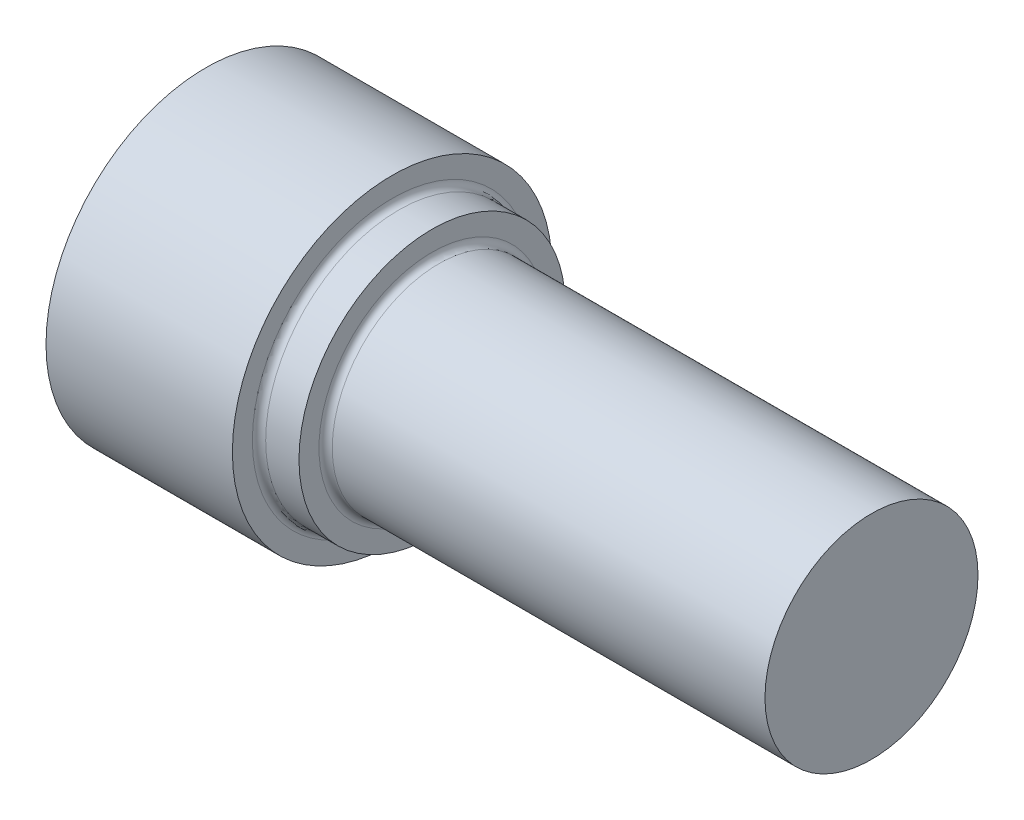
SolidWorks part; units mm, degrees
material "Alloy Steel"
ref_plane "Front Plane" through (0, 0, 0) normal (0, 0, 1) x (1, 0, 0)
ref_plane "Top Plane" through (0, 0, 0) normal (0, 1, 0) x (1, 0, 0)
ref_plane "Right Plane" through (0, 0, 0) normal (1, 0, 0) x (0, 0, -1)
sketch "Sketch1" plane through (0, 0, 0) normal (1, 0, 0) x (0, 0, -1)
  circle A0 centre (0, 0) radius 12
  dimension "D1" = 24
extrude "Boss-Extrude1" add sketch "Sketch1" along normal blind 14 contours A0
sketch "Sketch2" plane through (14, 0, 0) normal (1, 0, 0) x (0, 0, -1)
  circle A0 centre (0, 0) radius 10
  dimension "D1" = 20
extrude "Boss-Extrude2" add sketch "Sketch2" along normal blind 3
sketch "Sketch3" plane through (17, 0, 0) normal (1, 0, 0) x (0, 0, -1)
  circle A0 centre (0, 0) radius 8
  dimension "D1" = 16
extrude "Boss-Extrude3" add sketch "Sketch3" along normal blind 33
fillet "Fillet1" radius 0.5 2 edges at (14, 0, -10) (17, 0, -8)
